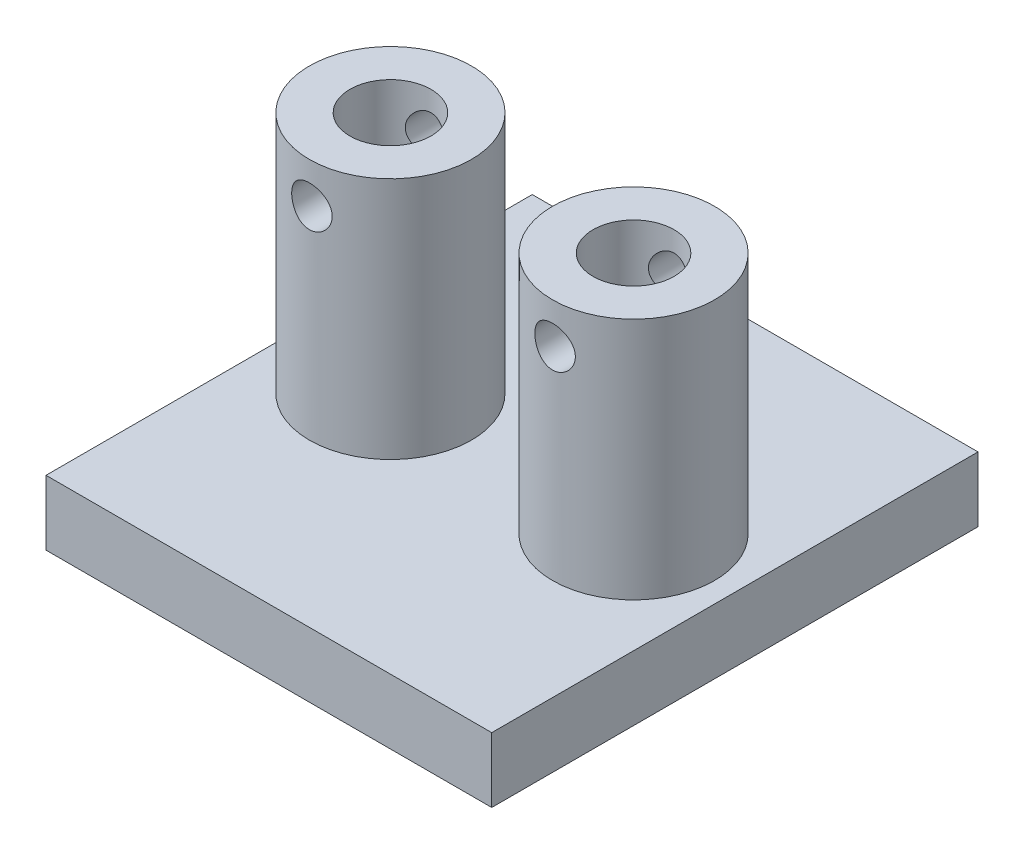
SolidWorks part; units mm, degrees
ref_plane "Front Plane" through (0, 0, 0) normal (0, 0, 1) x (1, 0, 0)
ref_plane "Top Plane" through (0, 0, 0) normal (0, 1, 0) x (1, 0, 0)
ref_plane "Right Plane" through (0, 0, 0) normal (1, 0, 0) x (0, 0, -1)
sketch "Sketch1" plane through (0, 0, 0) normal (0, 1, 0) x (1, 0, 0)
  line L1 (-5.5, 6) -> (5.5, 6)
  line L2 (-5.5, 6) -> (-5.5, -6)
  line L3 (-5.5, -6) -> (5.5, -6)
  line L4 (5.5, 6) -> (5.5, -6)
  line L5 (-5.5, 6) -> (5.5, -6) construction
  line L6 (-5.5, -6) -> (5.5, 6) construction
  point P0 (0, 0)
  dimension "D1" = 12
  dimension "D2" = 11
extrude "Boss-Extrude1" add sketch "Sketch1" along normal blind 1.6
sketch "Sketch2" plane through (0, 1.6, 0) normal (0, 1, 0) x (1, 0, 0)
  line L0 (-3, 0) -> (3, 0) construction
  circle A0 centre (-3, 0) radius 2
  circle A1 centre (3, 0) radius 2
  circle A7 centre (-3, 0) radius 1
  circle A8 centre (3, 0) radius 1
  circle A12 centre (9, 0) radius 2 [skipped]
  point P2 (0, 0)
  dimension "D1" = 4
  dimension "D3" = 6
  dimension "D2" = 3
extrude "Boss-Extrude2" add sketch "Sketch2" along normal blind 6
sketch "Sketch3" plane through (0, 0, 0) normal (0, 0, 1) x (1, 0, 0)
  line L0 (-3, 7.6) -> (-3, 6.6) construction
  line L1 (-1, 7.6) -> (-5, 7.6) construction
  circle A0 centre (-3, 6.6) radius 0.5
  circle A1 centre (3, 6.6) radius 0.5
  dimension "D1" = 1
  dimension "D2" = 1
extrude "Cut-Extrude1" cut sketch "Sketch3" against normal blind 2 and the other way blind 2
